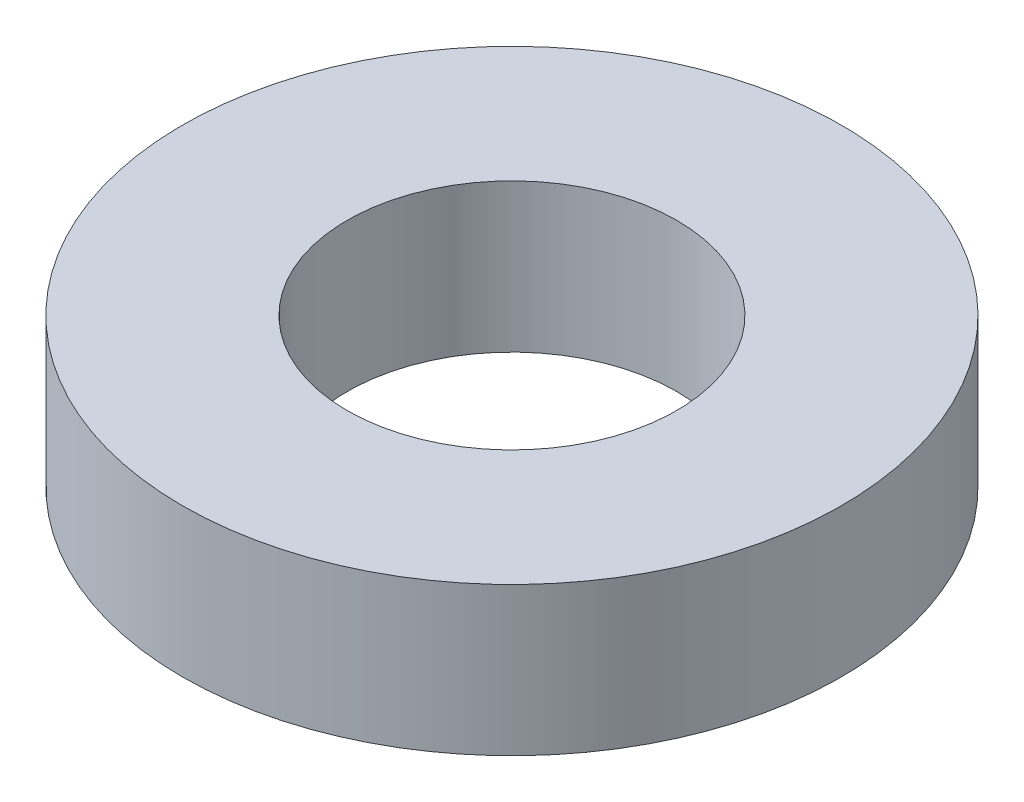
SolidWorks part; units mm, degrees
ref_plane "Front Plane" through (0, 0, 0) normal (0, 0, 1) x (1, 0, 0)
ref_plane "Top Plane" through (0, 0, 0) normal (0, 1, 0) x (1, 0, 0)
ref_plane "Right Plane" through (0, 0, 0) normal (1, 0, 0) x (0, 0, -1)
sketch "Sketch1" plane through (0, 0, 0) normal (0, 1, 0) x (1, 0, 0)
  circle A0 centre (0, 0) radius 20
  circle A1 centre (0, 0) radius 40
  dimension "D1" = 40
  dimension "D2" = 80
extrude "Boss-Extrude1" add sketch "Sketch1" along normal blind 18
